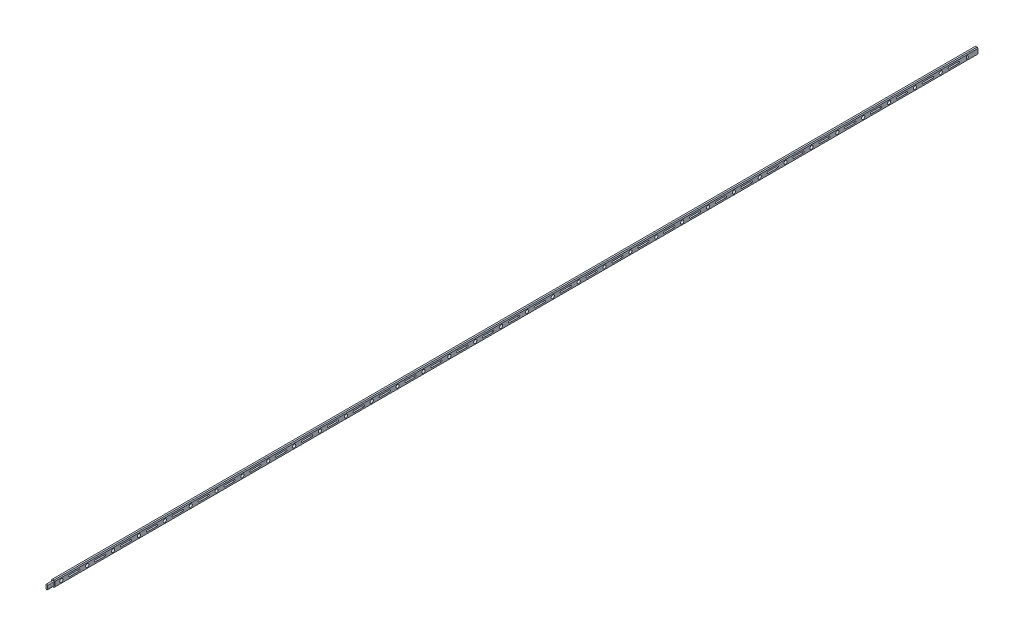
SolidWorks part; units mm, degrees
material "6061-T6 (SS)"
ref_plane "Front Plane" through (0, 0, 0) normal (0, 0, 1) x (1, 0, 0)
ref_plane "Top Plane" through (0, 0, 0) normal (0, 1, 0) x (1, 0, 0)
ref_plane "Right Plane" through (0, 0, 0) normal (1, 0, 0) x (0, 0, -1)
sketch "Sketch1" plane through (0, 0, 0) normal (0, 0, 1) x (1, 0, 0)
  line L0 (0, 11.1125) -> (1.5875, 12.7)
  line L1 (1.5875, 0) -> (4.7625, 0)
  line L2 (0, 1.5875) -> (0, 11.1125)
  line L3 (1.5875, 12.7) -> (4.7625, 12.7)
  line L4 (6.35, 1.5875) -> (6.35, 11.1125)
  line L5 (4.7625, 12.7) -> (6.35, 11.1125)
  line L6 (4.7625, 0) -> (6.35, 1.5875)
  line L7 (0, 1.5875) -> (1.5875, 0)
  point P0 (0, 0)
  point P1 (6.35, 12.7)
  point P2 (0, 12.7)
  point P3 (6.35, 0)
  dimension "D1" = 6.35
  dimension "D2" = 12.7
extrude "Boss-Extrude2" add sketch "Sketch1" along normal blind 1816.1
sketch "Sketch2" plane through (0, 0, 1816.1) normal (0, 0, 1) x (1, 0, 0)
  line L0 (0, 6.35) -> (6.35, 6.35) construction
  line L1 (0, 11.1125) -> (0, 1.5875) construction
  line L2 (6.35, 1.5875) -> (6.35, 11.1125) construction
  line L3 (3.175, 9.525) -> (3.175, 3.175) construction
  line L4 (1.5875, 0) -> (4.7625, 0) construction
  line L5 (3.175, 0) -> (3.175, 12.7) construction
  line L6 (4.7625, 12.7) -> (1.5875, 12.7) construction
  line L7 (4.7625, 9.525) -> (4.7625, 3.175)
  line L8 (1.5875, 9.525) -> (1.5875, 3.175)
  arc A0 (4.7625, 9.525) -> (1.5875, 9.525) centre (3.175, 9.525) ccw
  arc A1 (1.5875, 3.175) -> (4.7625, 3.175) centre (3.175, 3.175) ccw
  point P14 (3.175, 6.35)
extrude "Boss-Extrude3" add sketch "Sketch2" along normal blind 12.7
sketch "Sketch3" plane through (6.35, 0, 0) normal (1, 0, 0) x (0, 0, -1)
  line L0 (-1816.1, 12.7) -> (0, 12.7) construction
  line L1 (0, 1.5875) -> (0, 11.1125) construction
  line L2 (-41.275, 6.35) -> (-60.325, 6.35) construction
  line L3 (-41.275, 4.7625) -> (-60.325, 4.7625)
  line L4 (-41.275, 7.9375) -> (-60.325, 7.9375)
  line L6 (-92.075, 6.35) -> (-111.125, 6.35) construction
  line L7 (-92.075, 4.7625) -> (-111.125, 4.7625)
  line L8 (-92.075, 7.9375) -> (-111.125, 7.9375)
  line L9 (-142.875, 6.35) -> (-161.925, 6.35) construction
  line L10 (-142.875, 4.7625) -> (-161.925, 4.7625)
  line L11 (-142.875, 7.9375) -> (-161.925, 7.9375)
  line L12 (-193.675, 6.35) -> (-212.725, 6.35) construction
  line L13 (-193.675, 4.7625) -> (-212.725, 4.7625)
  line L14 (-193.675, 7.9375) -> (-212.725, 7.9375)
  line L15 (-244.475, 6.35) -> (-263.525, 6.35) construction
  line L16 (-244.475, 4.7625) -> (-263.525, 4.7625)
  line L17 (-244.475, 7.9375) -> (-263.525, 7.9375)
  line L18 (-295.275, 6.35) -> (-314.325, 6.35) construction
  line L19 (-295.275, 4.7625) -> (-314.325, 4.7625)
  line L20 (-295.275, 7.9375) -> (-314.325, 7.9375)
  line L21 (-346.075, 6.35) -> (-365.125, 6.35) construction
  line L22 (-346.075, 4.7625) -> (-365.125, 4.7625)
  line L23 (-346.075, 7.9375) -> (-365.125, 7.9375)
  line L24 (-396.875, 6.35) -> (-415.925, 6.35) construction
  line L25 (-396.875, 4.7625) -> (-415.925, 4.7625)
  line L26 (-396.875, 7.9375) -> (-415.925, 7.9375)
  line L27 (-447.675, 6.35) -> (-466.725, 6.35) construction
  line L28 (-447.675, 4.7625) -> (-466.725, 4.7625)
  line L29 (-447.675, 7.9375) -> (-466.725, 7.9375)
  line L30 (-498.475, 6.35) -> (-517.525, 6.35) construction
  line L31 (-498.475, 4.7625) -> (-517.525, 4.7625)
  line L32 (-498.475, 7.9375) -> (-517.525, 7.9375)
  line L33 (-549.275, 6.35) -> (-568.325, 6.35) construction
  line L34 (-549.275, 4.7625) -> (-568.325, 4.7625)
  line L35 (-549.275, 7.9375) -> (-568.325, 7.9375)
  line L36 (-600.075, 6.35) -> (-619.125, 6.35) construction
  line L37 (-600.075, 4.7625) -> (-619.125, 4.7625)
  line L38 (-600.075, 7.9375) -> (-619.125, 7.9375)
  line L39 (-650.875, 6.35) -> (-669.925, 6.35) construction
  line L40 (-650.875, 4.7625) -> (-669.925, 4.7625)
  line L41 (-650.875, 7.9375) -> (-669.925, 7.9375)
  line L42 (-701.675, 6.35) -> (-720.725, 6.35) construction
  line L43 (-701.675, 4.7625) -> (-720.725, 4.7625)
  line L44 (-701.675, 7.9375) -> (-720.725, 7.9375)
  line L45 (-752.475, 6.35) -> (-771.525, 6.35) construction
  line L46 (-752.475, 4.7625) -> (-771.525, 4.7625)
  line L47 (-752.475, 7.9375) -> (-771.525, 7.9375)
  line L48 (-803.275, 6.35) -> (-822.325, 6.35) construction
  line L49 (-803.275, 4.7625) -> (-822.325, 4.7625)
  line L50 (-803.275, 7.9375) -> (-822.325, 7.9375)
  line L51 (-854.075, 6.35) -> (-873.125, 6.35) construction
  line L52 (-854.075, 4.7625) -> (-873.125, 4.7625)
  line L53 (-854.075, 7.9375) -> (-873.125, 7.9375)
  line L54 (-904.875, 6.35) -> (-923.925, 6.35) construction
  line L55 (-904.875, 4.7625) -> (-923.925, 4.7625)
  line L56 (-904.875, 7.9375) -> (-923.925, 7.9375)
  line L57 (-955.675, 6.35) -> (-974.725, 6.35) construction
  line L58 (-955.675, 4.7625) -> (-974.725, 4.7625)
  line L59 (-955.675, 7.9375) -> (-974.725, 7.9375)
  line L60 (-1006.475, 6.35) -> (-1025.525, 6.35) construction
  line L61 (-1006.475, 4.7625) -> (-1025.525, 4.7625)
  line L62 (-1006.475, 7.9375) -> (-1025.525, 7.9375)
  line L63 (-1057.275, 6.35) -> (-1076.325, 6.35) construction
  line L64 (-1057.275, 4.7625) -> (-1076.325, 4.7625)
  line L65 (-1057.275, 7.9375) -> (-1076.325, 7.9375)
  line L66 (-1108.075, 6.35) -> (-1127.125, 6.35) construction
  line L67 (-1108.075, 4.7625) -> (-1127.125, 4.7625)
  line L68 (-1108.075, 7.9375) -> (-1127.125, 7.9375)
  line L69 (-1158.875, 6.35) -> (-1177.925, 6.35) construction
  line L70 (-1158.875, 4.7625) -> (-1177.925, 4.7625)
  line L71 (-1158.875, 7.9375) -> (-1177.925, 7.9375)
  line L72 (-1209.675, 6.35) -> (-1228.725, 6.35) construction
  line L73 (-1209.675, 4.7625) -> (-1228.725, 4.7625)
  line L74 (-1209.675, 7.9375) -> (-1228.725, 7.9375)
  line L75 (-1260.475, 6.35) -> (-1279.525, 6.35) construction
  line L76 (-1260.475, 4.7625) -> (-1279.525, 4.7625)
  line L77 (-1260.475, 7.9375) -> (-1279.525, 7.9375)
  line L78 (-1311.275, 6.35) -> (-1330.325, 6.35) construction
  line L79 (-1311.275, 4.7625) -> (-1330.325, 4.7625)
  line L80 (-1311.275, 7.9375) -> (-1330.325, 7.9375)
  line L81 (-1362.075, 6.35) -> (-1381.125, 6.35) construction
  line L82 (-1362.075, 4.7625) -> (-1381.125, 4.7625)
  line L83 (-1362.075, 7.9375) -> (-1381.125, 7.9375)
  line L84 (-1412.875, 6.35) -> (-1431.925, 6.35) construction
  line L85 (-1412.875, 4.7625) -> (-1431.925, 4.7625)
  line L86 (-1412.875, 7.9375) -> (-1431.925, 7.9375)
  line L87 (-1463.675, 6.35) -> (-1482.725, 6.35) construction
  line L88 (-1463.675, 4.7625) -> (-1482.725, 4.7625)
  line L89 (-1463.675, 7.9375) -> (-1482.725, 7.9375)
  line L90 (-1514.475, 6.35) -> (-1533.525, 6.35) construction
  line L91 (-1514.475, 4.7625) -> (-1533.525, 4.7625)
  line L92 (-1514.475, 7.9375) -> (-1533.525, 7.9375)
  line L93 (-1565.275, 6.35) -> (-1584.325, 6.35) construction
  line L94 (-1565.275, 4.7625) -> (-1584.325, 4.7625)
  line L95 (-1565.275, 7.9375) -> (-1584.325, 7.9375)
  line L96 (-1616.075, 6.35) -> (-1635.125, 6.35) construction
  line L97 (-1616.075, 4.7625) -> (-1635.125, 4.7625)
  line L98 (-1616.075, 7.9375) -> (-1635.125, 7.9375)
  line L99 (-1666.875, 6.35) -> (-1685.925, 6.35) construction
  line L100 (-1666.875, 4.7625) -> (-1685.925, 4.7625)
  line L101 (-1666.875, 7.9375) -> (-1685.925, 7.9375)
  line L102 (-1717.675, 6.35) -> (-1736.725, 6.35) construction
  line L103 (-1717.675, 4.7625) -> (-1736.725, 4.7625)
  line L104 (-1717.675, 7.9375) -> (-1736.725, 7.9375)
  line L105 (-1768.475, 6.35) -> (-1787.525, 6.35) construction
  line L106 (-1768.475, 4.7625) -> (-1787.525, 4.7625)
  line L107 (-1768.475, 7.9375) -> (-1787.525, 7.9375)
  line L114 (-1819.275, 6.35) -> (-1838.325, 6.35) construction
  line L115 (-1819.275, 4.7625) -> (-1838.325, 4.7625) [skipped]
  line L116 (-1819.275, 7.9375) -> (-1838.325, 7.9375) [skipped]
  line L117 (-1819.275, 6.35) -> (-1838.325, 6.35) construction
  line L118 (-1819.275, 4.7625) -> (-1838.325, 4.7625) [skipped]
  line L119 (-1819.275, 7.9375) -> (-1838.325, 7.9375) [skipped]
  circle A0 centre (-25.4, 6.35) radius 1.5875
  arc A1 (-41.275, 4.7625) -> (-41.275, 7.9375) centre (-41.275, 6.35) ccw
  arc A2 (-60.325, 7.9375) -> (-60.325, 4.7625) centre (-60.325, 6.35) ccw
  circle A3 centre (-76.2, 6.35) radius 1.5875
  arc A4 (-92.075, 4.7625) -> (-92.075, 7.9375) centre (-92.075, 6.35) ccw
  arc A5 (-111.125, 7.9375) -> (-111.125, 4.7625) centre (-111.125, 6.35) ccw
  circle A6 centre (-127, 6.35) radius 1.5875
  arc A7 (-142.875, 4.7625) -> (-142.875, 7.9375) centre (-142.875, 6.35) ccw
  arc A8 (-161.925, 7.9375) -> (-161.925, 4.7625) centre (-161.925, 6.35) ccw
  circle A9 centre (-177.8, 6.35) radius 1.5875
  arc A10 (-193.675, 4.7625) -> (-193.675, 7.9375) centre (-193.675, 6.35) ccw
  arc A11 (-212.725, 7.9375) -> (-212.725, 4.7625) centre (-212.725, 6.35) ccw
  circle A12 centre (-228.6, 6.35) radius 1.5875
  arc A13 (-244.475, 4.7625) -> (-244.475, 7.9375) centre (-244.475, 6.35) ccw
  arc A14 (-263.525, 7.9375) -> (-263.525, 4.7625) centre (-263.525, 6.35) ccw
  circle A15 centre (-279.4, 6.35) radius 1.5875
  arc A16 (-295.275, 4.7625) -> (-295.275, 7.9375) centre (-295.275, 6.35) ccw
  arc A17 (-314.325, 7.9375) -> (-314.325, 4.7625) centre (-314.325, 6.35) ccw
  circle A18 centre (-330.2, 6.35) radius 1.5875
  arc A19 (-346.075, 4.7625) -> (-346.075, 7.9375) centre (-346.075, 6.35) ccw
  arc A20 (-365.125, 7.9375) -> (-365.125, 4.7625) centre (-365.125, 6.35) ccw
  circle A21 centre (-381, 6.35) radius 1.5875
  arc A22 (-396.875, 4.7625) -> (-396.875, 7.9375) centre (-396.875, 6.35) ccw
  arc A23 (-415.925, 7.9375) -> (-415.925, 4.7625) centre (-415.925, 6.35) ccw
  circle A24 centre (-431.8, 6.35) radius 1.5875
  arc A25 (-447.675, 4.7625) -> (-447.675, 7.9375) centre (-447.675, 6.35) ccw
  arc A26 (-466.725, 7.9375) -> (-466.725, 4.7625) centre (-466.725, 6.35) ccw
  circle A27 centre (-482.6, 6.35) radius 1.5875
  arc A28 (-498.475, 4.7625) -> (-498.475, 7.9375) centre (-498.475, 6.35) ccw
  arc A29 (-517.525, 7.9375) -> (-517.525, 4.7625) centre (-517.525, 6.35) ccw
  circle A30 centre (-533.4, 6.35) radius 1.5875
  arc A31 (-549.275, 4.7625) -> (-549.275, 7.9375) centre (-549.275, 6.35) ccw
  arc A32 (-568.325, 7.9375) -> (-568.325, 4.7625) centre (-568.325, 6.35) ccw
  circle A33 centre (-584.2, 6.35) radius 1.5875
  arc A34 (-600.075, 4.7625) -> (-600.075, 7.9375) centre (-600.075, 6.35) ccw
  arc A35 (-619.125, 7.9375) -> (-619.125, 4.7625) centre (-619.125, 6.35) ccw
  circle A36 centre (-635, 6.35) radius 1.5875
  arc A37 (-650.875, 4.7625) -> (-650.875, 7.9375) centre (-650.875, 6.35) ccw
  arc A38 (-669.925, 7.9375) -> (-669.925, 4.7625) centre (-669.925, 6.35) ccw
  circle A39 centre (-685.8, 6.35) radius 1.5875
  arc A40 (-701.675, 4.7625) -> (-701.675, 7.9375) centre (-701.675, 6.35) ccw
  arc A41 (-720.725, 7.9375) -> (-720.725, 4.7625) centre (-720.725, 6.35) ccw
  circle A42 centre (-736.6, 6.35) radius 1.5875
  arc A43 (-752.475, 4.7625) -> (-752.475, 7.9375) centre (-752.475, 6.35) ccw
  arc A44 (-771.525, 7.9375) -> (-771.525, 4.7625) centre (-771.525, 6.35) ccw
  circle A45 centre (-787.4, 6.35) radius 1.5875
  arc A46 (-803.275, 4.7625) -> (-803.275, 7.9375) centre (-803.275, 6.35) ccw
  arc A47 (-822.325, 7.9375) -> (-822.325, 4.7625) centre (-822.325, 6.35) ccw
  circle A48 centre (-838.2, 6.35) radius 1.5875
  arc A49 (-854.075, 4.7625) -> (-854.075, 7.9375) centre (-854.075, 6.35) ccw
  arc A50 (-873.125, 7.9375) -> (-873.125, 4.7625) centre (-873.125, 6.35) ccw
  circle A51 centre (-889, 6.35) radius 1.5875
  arc A52 (-904.875, 4.7625) -> (-904.875, 7.9375) centre (-904.875, 6.35) ccw
  arc A53 (-923.925, 7.9375) -> (-923.925, 4.7625) centre (-923.925, 6.35) ccw
  circle A54 centre (-939.8, 6.35) radius 1.5875
  arc A55 (-955.675, 4.7625) -> (-955.675, 7.9375) centre (-955.675, 6.35) ccw
  arc A56 (-974.725, 7.9375) -> (-974.725, 4.7625) centre (-974.725, 6.35) ccw
  circle A57 centre (-990.6, 6.35) radius 1.5875
  arc A58 (-1006.475, 4.7625) -> (-1006.475, 7.9375) centre (-1006.475, 6.35) ccw
  arc A59 (-1025.525, 7.9375) -> (-1025.525, 4.7625) centre (-1025.525, 6.35) ccw
  circle A60 centre (-1041.4, 6.35) radius 1.5875
  arc A61 (-1057.275, 4.7625) -> (-1057.275, 7.9375) centre (-1057.275, 6.35) ccw
  arc A62 (-1076.325, 7.9375) -> (-1076.325, 4.7625) centre (-1076.325, 6.35) ccw
  circle A63 centre (-1092.2, 6.35) radius 1.5875
  arc A64 (-1108.075, 4.7625) -> (-1108.075, 7.9375) centre (-1108.075, 6.35) ccw
  arc A65 (-1127.125, 7.9375) -> (-1127.125, 4.7625) centre (-1127.125, 6.35) ccw
  circle A66 centre (-1143, 6.35) radius 1.5875
  arc A67 (-1158.875, 4.7625) -> (-1158.875, 7.9375) centre (-1158.875, 6.35) ccw
  arc A68 (-1177.925, 7.9375) -> (-1177.925, 4.7625) centre (-1177.925, 6.35) ccw
  circle A69 centre (-1193.8, 6.35) radius 1.5875
  arc A70 (-1209.675, 4.7625) -> (-1209.675, 7.9375) centre (-1209.675, 6.35) ccw
  arc A71 (-1228.725, 7.9375) -> (-1228.725, 4.7625) centre (-1228.725, 6.35) ccw
  circle A72 centre (-1244.6, 6.35) radius 1.5875
  arc A73 (-1260.475, 4.7625) -> (-1260.475, 7.9375) centre (-1260.475, 6.35) ccw
  arc A74 (-1279.525, 7.9375) -> (-1279.525, 4.7625) centre (-1279.525, 6.35) ccw
  circle A75 centre (-1295.4, 6.35) radius 1.5875
  arc A76 (-1311.275, 4.7625) -> (-1311.275, 7.9375) centre (-1311.275, 6.35) ccw
  arc A77 (-1330.325, 7.9375) -> (-1330.325, 4.7625) centre (-1330.325, 6.35) ccw
  circle A78 centre (-1346.2, 6.35) radius 1.5875
  arc A79 (-1362.075, 4.7625) -> (-1362.075, 7.9375) centre (-1362.075, 6.35) ccw
  arc A80 (-1381.125, 7.9375) -> (-1381.125, 4.7625) centre (-1381.125, 6.35) ccw
  circle A81 centre (-1397, 6.35) radius 1.5875
  arc A82 (-1412.875, 4.7625) -> (-1412.875, 7.9375) centre (-1412.875, 6.35) ccw
  arc A83 (-1431.925, 7.9375) -> (-1431.925, 4.7625) centre (-1431.925, 6.35) ccw
  circle A84 centre (-1447.8, 6.35) radius 1.5875
  arc A85 (-1463.675, 4.7625) -> (-1463.675, 7.9375) centre (-1463.675, 6.35) ccw
  arc A86 (-1482.725, 7.9375) -> (-1482.725, 4.7625) centre (-1482.725, 6.35) ccw
  circle A87 centre (-1498.6, 6.35) radius 1.5875
  arc A88 (-1514.475, 4.7625) -> (-1514.475, 7.9375) centre (-1514.475, 6.35) ccw
  arc A89 (-1533.525, 7.9375) -> (-1533.525, 4.7625) centre (-1533.525, 6.35) ccw
  circle A90 centre (-1549.4, 6.35) radius 1.5875
  arc A91 (-1565.275, 4.7625) -> (-1565.275, 7.9375) centre (-1565.275, 6.35) ccw
  arc A92 (-1584.325, 7.9375) -> (-1584.325, 4.7625) centre (-1584.325, 6.35) ccw
  circle A93 centre (-1600.2, 6.35) radius 1.5875
  arc A94 (-1616.075, 4.7625) -> (-1616.075, 7.9375) centre (-1616.075, 6.35) ccw
  arc A95 (-1635.125, 7.9375) -> (-1635.125, 4.7625) centre (-1635.125, 6.35) ccw
  circle A96 centre (-1651, 6.35) radius 1.5875
  arc A97 (-1666.875, 4.7625) -> (-1666.875, 7.9375) centre (-1666.875, 6.35) ccw
  arc A98 (-1685.925, 7.9375) -> (-1685.925, 4.7625) centre (-1685.925, 6.35) ccw
  circle A99 centre (-1701.8, 6.35) radius 1.5875
  arc A100 (-1717.675, 4.7625) -> (-1717.675, 7.9375) centre (-1717.675, 6.35) ccw
  arc A101 (-1736.725, 7.9375) -> (-1736.725, 4.7625) centre (-1736.725, 6.35) ccw
  circle A102 centre (-1752.6, 6.35) radius 1.5875
  arc A103 (-1768.475, 4.7625) -> (-1768.475, 7.9375) centre (-1768.475, 6.35) ccw
  arc A104 (-1787.525, 7.9375) -> (-1787.525, 4.7625) centre (-1787.525, 6.35) ccw
  circle A105 centre (-1803.4, 6.35) radius 1.5875
  arc A112 (-1819.275, 4.7625) -> (-1819.275, 7.9375) centre (-1819.275, 6.35) ccw [skipped]
  arc A113 (-1838.325, 7.9375) -> (-1838.325, 4.7625) centre (-1838.325, 6.35) ccw [skipped]
  point P8 (-50.8, 6.35)
  point P19 (-101.6, 6.35)
  point P28 (-152.4, 6.35)
  point P37 (-203.2, 6.35)
  point P46 (-254, 6.35)
  point P55 (-304.8, 6.35)
  point P64 (-355.6, 6.35)
  point P73 (-406.4, 6.35)
  point P82 (-457.2, 6.35)
  point P91 (-508, 6.35)
  point P100 (-558.8, 6.35)
  point P109 (-609.6, 6.35)
  point P118 (-660.4, 6.35)
  point P127 (-711.2, 6.35)
  point P136 (-762, 6.35)
  point P145 (-812.8, 6.35)
  point P154 (-863.6, 6.35)
  point P163 (-914.4, 6.35)
  point P172 (-965.2, 6.35)
  point P181 (-1016, 6.35)
  point P190 (-1066.8, 6.35)
  point P199 (-1117.6, 6.35)
  point P208 (-1168.4, 6.35)
  point P217 (-1219.2, 6.35)
  point P226 (-1270, 6.35)
  point P235 (-1320.8, 6.35)
  point P244 (-1371.6, 6.35)
  point P253 (-1422.4, 6.35)
  point P262 (-1473.2, 6.35)
  point P271 (-1524, 6.35)
  point P280 (-1574.8, 6.35)
  point P289 (-1625.6, 6.35)
  point P298 (-1676.4, 6.35)
  point P307 (-1727.2, 6.35)
  point P316 (-1778, 6.35)
  point P330 (-1828.8, 6.35)
  point P337 (-1828.8, 6.35)
  point P344 (-1828.8, 6.35)
  dimension "D1" = 3.175
  dimension "D4" = 50.8
  dimension "D2" = 6.35
  dimension "D3" = 25.4
  dimension "D5" = 19.05
  dimension "D6" = 36
extrude "Cut-Extrude1" cut sketch "Sketch3" against normal blind 70.358
sketch "Sketch4" plane through (0, 0, 0) normal (-1, 0, 0) x (0, 0, 1)
  circle A0 centre (1803.4, 6.35) radius 3.175
  circle A1 centre (1752.6, 6.35) radius 3.175
  circle A2 centre (1701.8, 6.35) radius 3.175
  circle A3 centre (1651, 6.35) radius 3.175
  circle A4 centre (1600.2, 6.35) radius 3.175
  circle A5 centre (1549.4, 6.35) radius 3.175
  circle A6 centre (1498.6, 6.35) radius 3.175
  circle A7 centre (1447.8, 6.35) radius 3.175
  circle A8 centre (1397, 6.35) radius 3.175
  circle A9 centre (1346.2, 6.35) radius 3.175
  circle A10 centre (1295.4, 6.35) radius 3.175
  circle A11 centre (1244.6, 6.35) radius 3.175
  circle A12 centre (1193.8, 6.35) radius 3.175
  circle A13 centre (1143, 6.35) radius 3.175
  circle A14 centre (1092.2, 6.35) radius 3.175
  circle A15 centre (1041.4, 6.35) radius 3.175
  circle A16 centre (990.6, 6.35) radius 3.175
  circle A17 centre (939.8, 6.35) radius 3.175
  circle A18 centre (889, 6.35) radius 3.175
  circle A19 centre (838.2, 6.35) radius 3.175
  circle A20 centre (787.4, 6.35) radius 3.175
  circle A21 centre (736.6, 6.35) radius 3.175
  circle A22 centre (685.8, 6.35) radius 3.175
  circle A23 centre (635, 6.35) radius 3.175
  circle A24 centre (584.2, 6.35) radius 3.175
  circle A25 centre (533.4, 6.35) radius 3.175
  circle A26 centre (482.6, 6.35) radius 3.175
  circle A27 centre (431.8, 6.35) radius 3.175
  circle A28 centre (381, 6.35) radius 3.175
  circle A29 centre (330.2, 6.35) radius 3.175
  circle A30 centre (279.4, 6.35) radius 3.175
  circle A31 centre (228.6, 6.35) radius 3.175
  circle A32 centre (177.8, 6.35) radius 3.175
  circle A33 centre (127, 6.35) radius 3.175
  circle A34 centre (76.2, 6.35) radius 3.175
  circle A35 centre (25.4, 6.35) radius 3.175
  dimension "D1" = 6.35
  dimension "D2" = 36
extrude "Cut-Extrude2" cut sketch "Sketch4" against normal through all
sketch "Sketch5" plane through (0, -6.35, 0) normal (0, -1, 0) x (-1, 0, 0)
  line L1 (196.85, -3.1586) -> (-58.3965, -3.1586)
  line L2 (196.85, -3.1586) -> (196.85, 18.7196)
  line L3 (196.85, 18.7196) -> (-58.3965, 18.7196)
  line L4 (-58.3965, -3.1586) -> (-58.3965, 18.7196)
extrude "Cut-Extrude3" cut sketch "Sketch5" against normal blind 254
sketch "Sketch6" plane through (0, 0, 0) normal (-1, 0, 0) x (0, 0, 1)
  line L1 (25.4, 9.525) -> (25.4, 3.175)
  arc A0 (25.4, 3.175) -> (25.4, 9.525) centre (25.4, 6.35) ccw
extrude "Boss-Extrude6" add sketch "Sketch6" against normal blind 6.35
